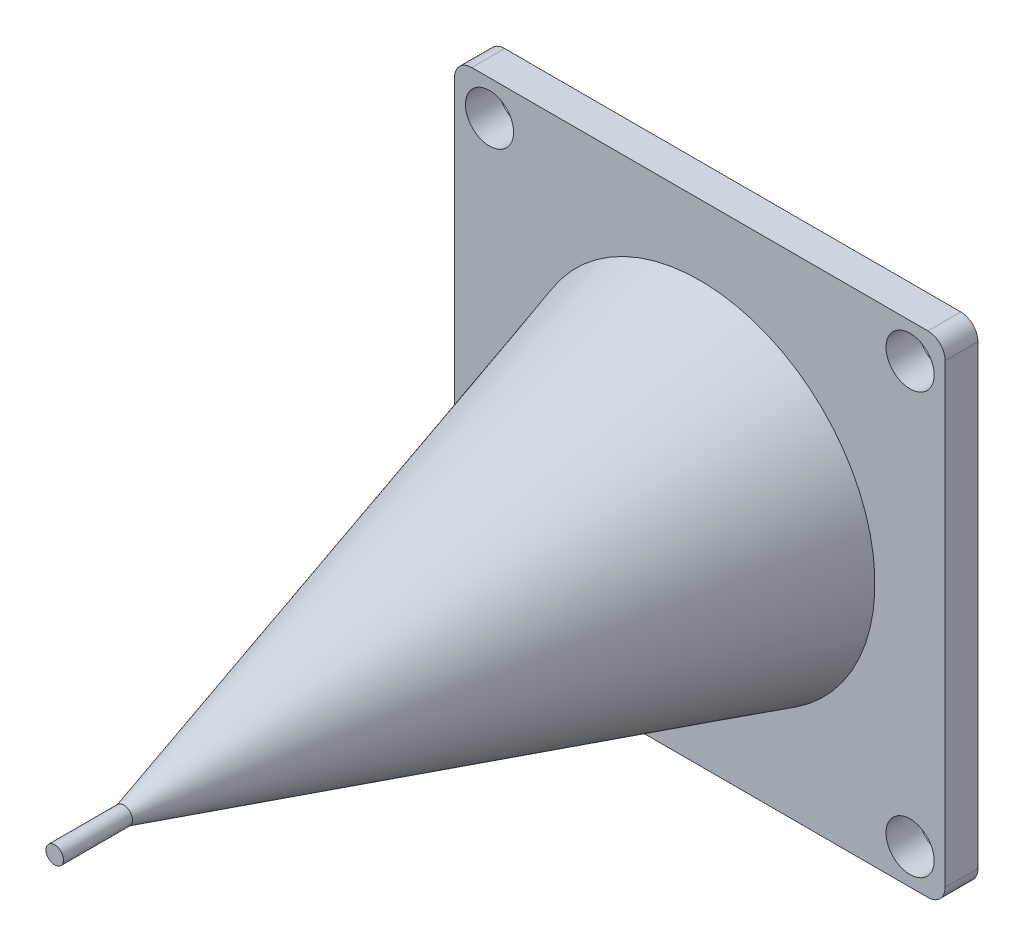
SolidWorks part; units mm, degrees
ref_plane "Front Plane" through (0, 0, 0) normal (0, 0, 1) x (1, 0, 0)
ref_plane "Top Plane" through (0, 0, 0) normal (0, 1, 0) x (1, 0, 0)
ref_plane "Right Plane" through (0, 0, 0) normal (1, 0, 0) x (0, 0, -1)
sketch "Sketch1" plane through (0, 0, 0) normal (0, 0, 1) x (1, 0, 0)
  line L1 (-35.56, 35.56) -> (35.56, 35.56)
  line L2 (-35.56, 35.56) -> (-35.56, -35.56)
  line L3 (-35.56, -35.56) -> (35.56, -35.56)
  line L4 (35.56, 35.56) -> (35.56, -35.56)
  dimension "D1" = 71.12
  dimension "D2" = 71.12
  dimension "D3" = 35.56
  dimension "D4" = 35.56
extrude "Boss-Extrude1" add sketch "Sketch1" along normal blind 4.7625
sketch "Sketch2" plane through (0, 0, 4.7625) normal (0, 0, 1) x (1, 0, 0)
  circle A0 centre (-30.48, 30.48) radius 3.4925
  circle A1 centre (30.48, 30.48) radius 3.4925
  dimension "D1" = 6.985
  dimension "D2" = 6.985
  dimension "D3" = 60.96
  dimension "D4" = 30.48
  dimension "D5" = 30.48
  dimension "D6" = 30.48
extrude "Cut-Extrude1" cut sketch "Sketch2" against normal through all
mirror "Mirror1" about plane through (0, 0, 0) normal (0, 1, 0) of "Cut-Extrude1"
sketch "Sketch3" plane through (0, 0, 4.7625) normal (0, 0, 1) x (1, 0, 0)
  circle A0 centre (0, 0) radius 25.382
  dimension "D1" = 50.764
extrude "Boss-Extrude2" add sketch "Sketch3" along normal blind 83.5
sketch "Sketch4" plane through (0, 0, 0) normal (1, 0, 0) x (0, 0, -1)
  line L0 (-4.7625, 25.382) -> (-88.2625, 1.245)
  line L1 (-4.7625, 25.382) -> (-4.7625, -25.382) construction
  line L2 (-4.7625, -35.56) -> (-4.7625, 35.56) construction
  line L3 (-88.2625, 25.382) -> (-88.2625, -25.382) construction
  line L7 (-88.2625, 25.382) -> (-88.2625, 1.245)
  line L8 (-4.7625, 25.382) -> (-88.2625, 25.382)
  line L9 (-88.2625, 0) -> (-4.7625, 0) construction
  dimension "D1" = 1.245
revolve "Cut-Revolve1" cut sketch "Sketch4" angle 360 about axis through (0, 0, 88.2625) along (0, 0, -1)
sketch "Sketch5" plane through (0, 0, 88.2625) normal (0, 0, 1) x (1, 0, 0)
  circle A0 centre (0, 0) radius 1.27
extrude "Boss-Extrude3" add sketch "Sketch5" along normal blind 10
fillet "Fillet1" radius 2.5 4 edges at (-35.56, 35.56, 2.3813) (-35.56, -35.56, 2.3813) (35.56, 35.56, 2.3813) (35.56, -35.56, 2.3813)
equation "\"D2@Sketch1\"=\"D1@Sketch1\""
equation "\"D3@Sketch1\"=\"D1@Sketch1\"/2"
equation "\"D4@Sketch1\"=\"D3@Sketch1\""
equation "\"D4@Sketch2\"=\"D3@Sketch2\"/2"
equation "\"D5@Sketch2\"=\"D4@Sketch2\""
equation "\"D6@Sketch2\"=\"D5@Sketch2\""
